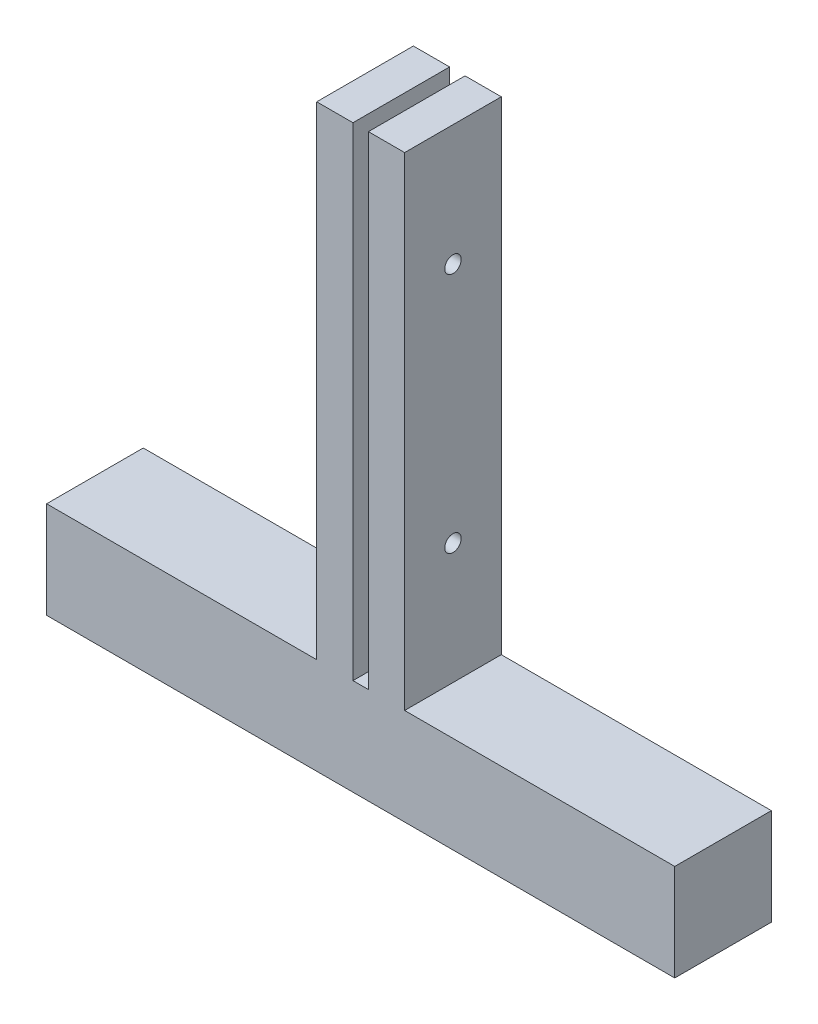
SolidWorks part; units mm, degrees
ref_plane "Front Plane" through (0, 0, 0) normal (0, 0, 1) x (1, 0, 0)
ref_plane "Top Plane" through (0, 0, 0) normal (0, 1, 0) x (1, 0, 0)
ref_plane "Right Plane" through (0, 0, 0) normal (1, 0, 0) x (0, 0, -1)
sketch "Sketch1" plane through (0, 0, 0) normal (0, 0, 1) x (1, 0, 0)
  line L0 (0, 0) -> (65, 0)
  line L1 (41.25, 0) -> (-41.25, 0) construction
  line L2 (65, 0) -> (65, 20)
  line L3 (65, 20) -> (9.1, 20)
  line L4 (9.1, 20) -> (9.1, 120)
  line L5 (9.1, 120) -> (1.6, 120)
  line L6 (1.6, 120) -> (1.6, 20)
  line L7 (1.6, 20) -> (-1.6, 20)
  line L8 (-1.6, 20) -> (-1.6, 120)
  line L9 (-1.6, 120) -> (-9.1, 120)
  line L10 (-9.1, 120) -> (-9.1, 20)
  line L11 (-9.1, 20) -> (-65, 20)
  line L12 (-65, 20) -> (-65, 0)
  line L13 (-65, 0) -> (0, 0)
  point P15 (0, 0)
  point P17 (0, 0)
  dimension "D1" = 65
  dimension "D2" = 20
  dimension "D3" = 55.9
  dimension "D4" = 100
  dimension "D5" = 7.5
  dimension "D6" = 3.2
  dimension "D7" = 130
  dimension "D8" = 7.5
extrude "Boss-Extrude3" add sketch "Sketch1" along normal blind 20
sketch "Sketch3" plane through (9.1, 0, 0) normal (1, 0, 0) x (0, 0, -1)
  circle A0 centre (-10, 95) radius 1.7
  circle A1 centre (-10, 45) radius 1.7
  point P0 (0, 0)
  dimension "D1" = 50
extrude "Cut-Extrude1" cut sketch "Sketch3" against normal blind 161 and the other way blind 88
